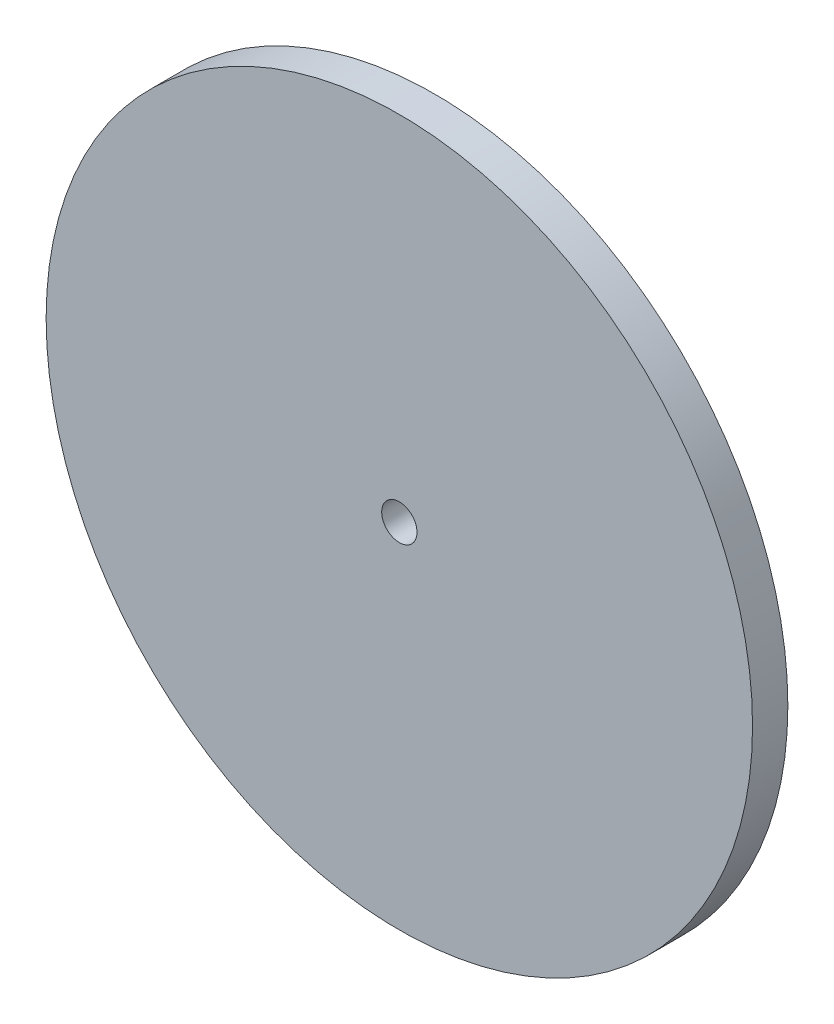
SolidWorks part; units mm, degrees
ref_plane "Front Plane" through (0, 0, 0) normal (0, 0, 1) x (1, 0, 0)
ref_plane "Top Plane" through (0, 0, 0) normal (0, 1, 0) x (1, 0, 0)
ref_plane "Right Plane" through (0, 0, 0) normal (1, 0, 0) x (0, 0, -1)
sketch "Sketch1" plane through (0, 0, 0) normal (0, 0, 1) x (1, 0, 0)
  circle A0 centre (0, 0) radius 63.5
  circle A1 centre (0, 0) radius 3.175
extrude "Boss-Extrude1" add sketch "Sketch1" along normal blind 6.35
